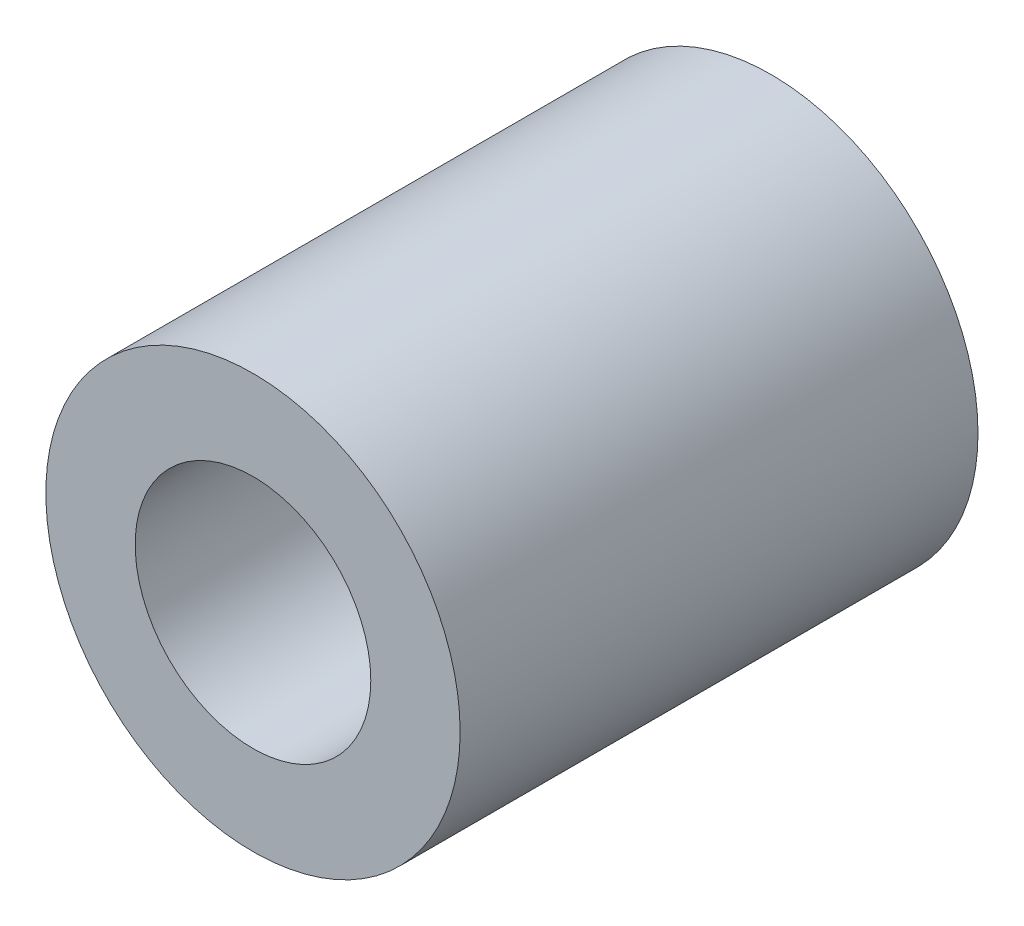
SolidWorks part; units mm, degrees
ref_plane "Front Plane" through (0, 0, 0) normal (0, 0, 1) x (1, 0, 0)
ref_plane "Top Plane" through (0, 0, 0) normal (0, 1, 0) x (1, 0, 0)
ref_plane "Right Plane" through (0, 0, 0) normal (1, 0, 0) x (0, 0, -1)
sketch "Sketch1" plane through (0, 0, 0) normal (0, 0, 1) x (1, 0, 0)
  circle A0 centre (0, 0) radius 2.275
  circle A1 centre (0, 0) radius 4
  dimension "D1" = 4.55
  dimension "D2" = 8
extrude "Boss-Extrude1" add sketch "Sketch1" along normal blind 10
